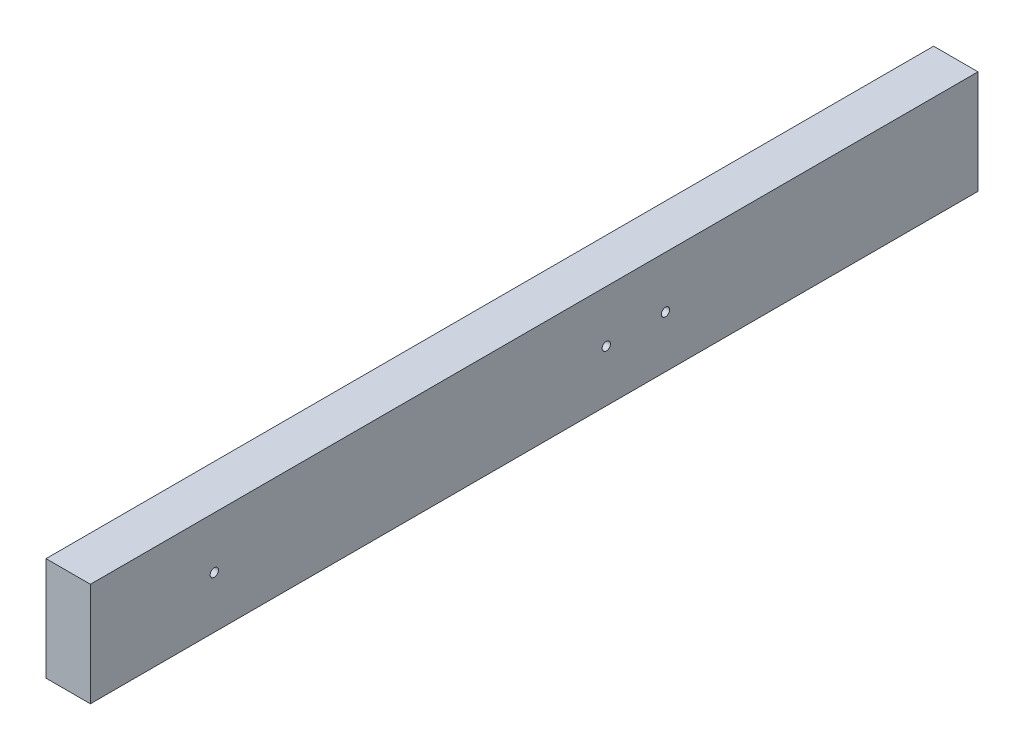
SolidWorks part; units mm, degrees
material "Pine"
ref_plane "Front Plane" through (0, 0, 0) normal (0, 0, 1) x (1, 0, 0)
ref_plane "Top Plane" through (0, 0, 0) normal (0, 1, 0) x (1, 0, 0)
ref_plane "Right Plane" through (0, 0, 0) normal (1, 0, 0) x (0, 0, -1)
sketch "Sketch1" plane through (0, 0, 0) normal (1, 0, 0) x (0, 0, -1)
  line L1 (0, 0) -> (762, 0)
  line L2 (0, 0) -> (0, 88.9)
  line L3 (0, 88.9) -> (762, 88.9)
  line L4 (762, 0) -> (762, 88.9)
  dimension "D1" = 88.9
  dimension "D2" = 762
extrude "Boss-Extrude1" add sketch "Sketch1" along normal blind 38.1
sketch "Sketch2" plane through (38.1, 0, 0) normal (1, 0, 0) x (0, 0, -1)
  line L0 (0, 88.9) -> (0, 0) construction
  line L1 (0, 0) -> (762, 0) construction
  line L2 (762, 88.9) -> (0, 88.9) construction
  circle A0 centre (106.393, 44.45) radius 3.5719
  circle A1 centre (442.9125, 44.45) radius 3.5719
  circle A2 centre (493.7125, 44.45) radius 3.5719
  dimension "D3" = 7.1437
  dimension "D6" = 7.1437
  dimension "D8" = 7.1437
  dimension "D9" = 44.45
  dimension "D1" = 106.393
  dimension "D2" = 44.45
  dimension "D4" = 442.9125
  dimension "D5" = 44.45
  dimension "D7" = 50.8
extrude "Cut-Extrude1" cut sketch "Sketch2" against normal through all
